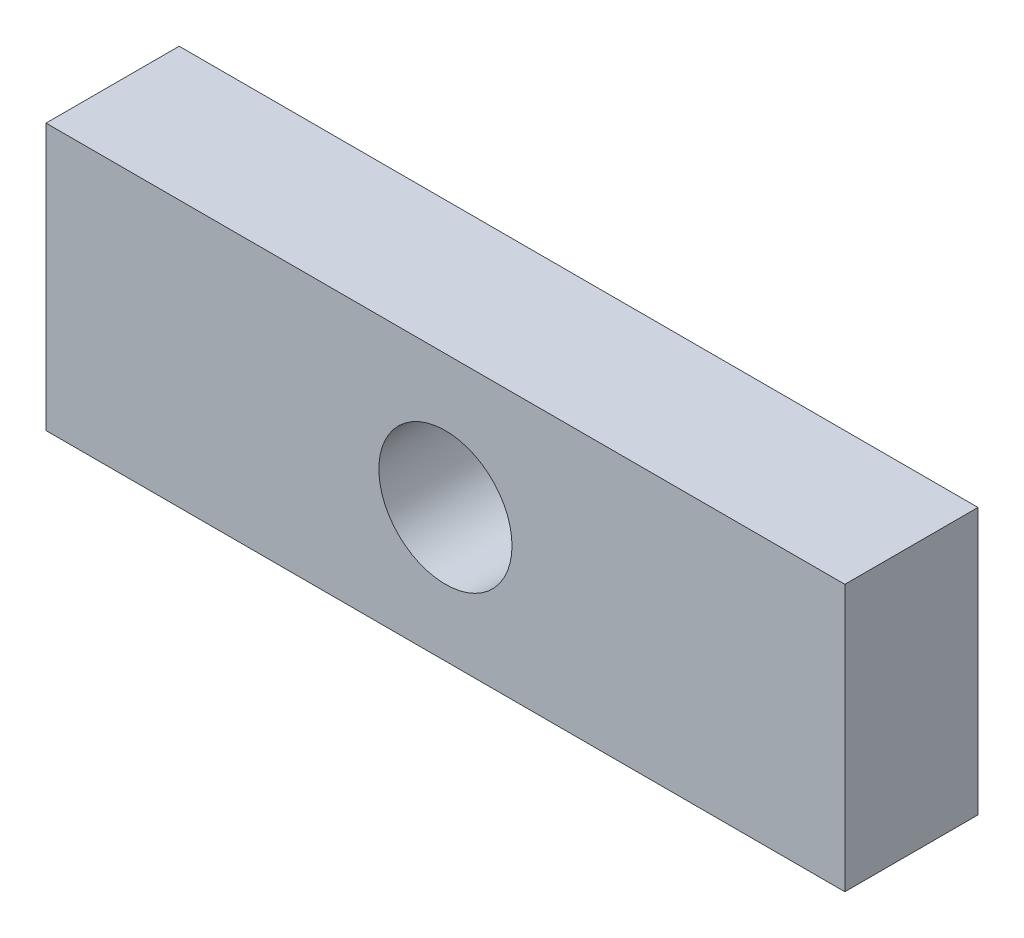
SolidWorks part; units mm, degrees
ref_plane "Front Plane" through (0, 0, 0) normal (0, 0, 1) x (1, 0, 0)
ref_plane "Top Plane" through (0, 0, 0) normal (0, 1, 0) x (1, 0, 0)
ref_plane "Right Plane" through (0, 0, 0) normal (1, 0, 0) x (0, 0, -1)
sketch "Sketch1" plane through (0, 0, 0) normal (0, 0, 1) x (1, 0, 0)
  line L1 (-30, 10) -> (30, 10)
  line L2 (-30, 10) -> (-30, -10)
  line L3 (-30, -10) -> (30, -10)
  line L4 (30, 10) -> (30, -10)
  line L5 (-30, 10) -> (30, -10) construction
  line L6 (-30, -10) -> (30, 10) construction
  circle A0 centre (0, 0) radius 5
  point P0 (0, 0)
  dimension "D1" = 10
  dimension "D2" = 20
  dimension "D3" = 60
extrude "Boss-Extrude1" add sketch "Sketch1" along normal blind 10
